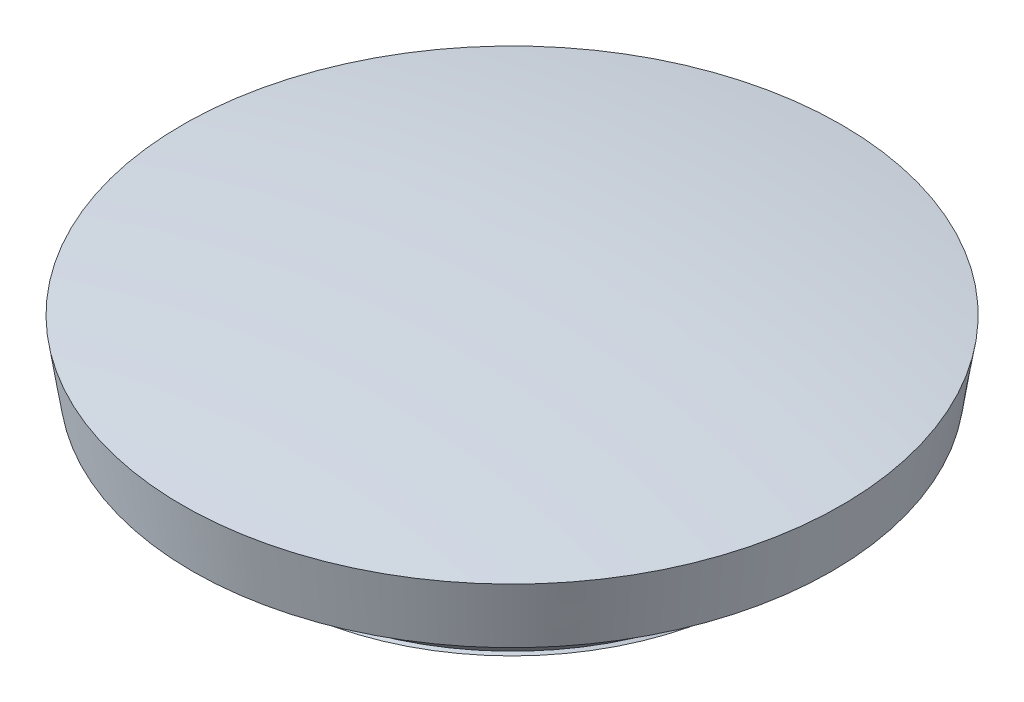
SolidWorks part; units mm, degrees
ref_plane "Front Plane" through (0, 0, 0) normal (0, 0, 1) x (1, 0, 0)
ref_plane "Top Plane" through (0, 0, 0) normal (0, 1, 0) x (1, 0, 0)
ref_plane "Right Plane" through (0, 0, 0) normal (1, 0, 0) x (0, 0, -1)
sketch "Sketch1" plane through (0, 0, 0) normal (1, 0, 0) x (0, 0, -1)
  line L0 (26.0878, 274.978) -> (26.0878, 232.1195) construction
  line L2 (40.135, 302.9291) -> (40.135, 295.6281) construction
  line L5 (0, 324) -> (3.2968, 324) construction
  line L7 (21.6442, 186.0993) -> (0, 186.0993) construction
  line L9 (26.0878, 262.3641) -> (26.0878, 259.4973) construction
  line L16 (0, 0) -> (51.9362, 327.9125) construction
  line L17 (0, 324) -> (0, 332) construction
  line L18 (26.0878, 274.978) -> (26.0878, 268.978) construction
  line L19 (26.0878, 268.978) -> (26.0878, 248.978) construction
  line L20 (26.0878, 268.978) -> (42.6019, 268.978) construction
  line L21 (26.0878, 274.978) -> (43.5522, 274.978) construction
  line L22 (26.0878, 248.978) -> (39.4342, 248.978) construction
  line L23 (0, 0) -> (-51.9362, 327.9125) construction
  line L24 (-47.4003, 299.274) -> (-47.4003, 268.978) construction
  line L25 (-47.4003, 268.978) -> (-42.6019, 268.978) construction
  line L26 (40.135, 295.6281) -> (40.435, 295.6281) construction
  line L27 (0, 76.96) -> (400, 76.96) construction
  line L28 (0, 76.96) -> (-400, 76.96) construction
  line L29 (-200, 76.96) -> (-200, 183.96) construction
  line L30 (200, 76.96) -> (200, 183.96) construction
  line L31 (-200, 183.96) -> (-200, 182.57) construction
  line L32 (-200, 182.57) -> (400, 182.57) construction
  line L33 (-200, 182.57) -> (-400, 182.57) construction
  line L36 (21.6442, 186.0993) -> (21.6442, 226.0993) construction
  line L37 (0, 324) -> (0, 186.1152) construction
  line L38 (0, 186.1152) -> (0, 186.0993)
  line L39 (0, 0) -> (-2, 0) construction
  line L40 (-2, 0) -> (49.9843, 328.2157) construction
  line L41 (51.9362, 327.9125) -> (49.9362, 327.9125) construction
  line L42 (26.0878, 274.978) -> (26.3878, 274.978) construction
  line L43 (26.0878, 274.978) -> (26.0878, 273.978) construction
  line L44 (26.2311, 276.2681) -> (26.5311, 276.2681) construction
  line L45 (26.6611, 277.4147) -> (26.9611, 277.4147) construction
  line L46 (27.2344, 278.5614) -> (27.5344, 278.5614) construction
  line L47 (27.9512, 279.4215) -> (28.2512, 279.4215) construction
  line L48 (28.9545, 280.5682) -> (29.2545, 280.5682) construction
  line L49 (29.8146, 281.4282) -> (30.1146, 281.4282) construction
  line L50 (30.8179, 282.4316) -> (31.1179, 282.4316) construction
  line L51 (31.8213, 283.2917) -> (32.1213, 283.2917) construction
  line L52 (32.8246, 284.2951) -> (33.1246, 284.2951) construction
  line L53 (33.8281, 285.2984) -> (34.1281, 285.2984) construction
  line L54 (34.9748, 286.3018) -> (35.2748, 286.3018) construction
  line L55 (35.9781, 287.3051) -> (36.2781, 287.3051) construction
  line L56 (36.8382, 288.1652) -> (37.1382, 288.1652) construction
  line L57 (37.8416, 289.3119) -> (38.1416, 289.3119) construction
  line L58 (38.5582, 290.4586) -> (38.8582, 290.4586) construction
  line L59 (39.1315, 291.7487) -> (39.4315, 291.7487) construction
  line L60 (39.5617, 292.8954) -> (39.8617, 292.8954) construction
  line L61 (39.8483, 294.0421) -> (40.1483, 294.0421) construction
  line L63 (40.135, 302.9291) -> (40.435, 302.9291) construction
  line L64 (26.0878, 273.978) -> (26.3878, 273.978) construction
  line L68 (0, 332) -> (36.0261, 332) construction
  line L69 (36.0261, 332) -> (36.0261, 309.4264) construction
  line L70 (36.0261, 309.4264) -> (48.951, 321.6917) construction
  line L71 (36.0261, 309.4264) -> (49.0083, 309.4264) construction
  line L73 (36.0261, 309.4264) -> (46.0928, 318.9794) construction
  line L74 (46.0928, 318.9794) -> (46.0928, 386.8005) construction
  line L75 (46.0928, 318.9794) -> (19.4833, 320.3739) construction
  line L76 (19.4833, 320.3739) -> (20.8454, 323.7133) construction
  line L77 (19.4833, 320.3739) -> (28.7426, 316.597) construction
  line L78 (19.4833, 320.3739) -> (10.2239, 324.1508) construction
  line L79 (10.2239, 324.1508) -> (9.7753, 323.0511) construction
  line L80 (28.7426, 316.597) -> (28.4187, 315.803) construction
  arc A0 (-298.7691, 144.7791) -> (305.6579, 129.6043) centre (0, 0) cw construction
  spline S0 degree 3 poles (21.6442, 226.0993) (22.3362, 225.9573) (23.1249, 226.5484) (24.2443, 227.206) (25.0066, 227.971) (25.5796, 228.9526) (25.8622, 230.3928) (26.0228, 231.4438) (26.0878, 232.1195) knots 0 0 0 0 0.223849 0.348959 0.47164 0.61152 0.754586 1 1 1 1 construction
  spline S1 degree 3 poles (3.2968, 324) (4.1972, 323.8396) (5.699, 323.816) (7.6935, 323.4297) (9.2722, 323.1563) (10.7507, 322.8538) (12.1816, 322.5577) (13.6372, 322.313) (14.8643, 321.9117) (15.9115, 321.5662) (16.81, 321.2491) (17.7339, 321.0149) (18.8379, 320.6416) (19.931, 320.1935) (21.0686, 319.6948) (22.141, 319.2627) (23.2156, 318.6856) (24.4371, 318.1163) (25.6762, 317.3518) (27.1066, 316.7518) (28.4318, 315.7832) (29.7322, 314.8939) (31.058, 313.93) (32.1959, 312.8581) (33.3378, 311.8503) (34.4539, 310.9646) (35.3895, 309.8867) (36.5078, 309.0949) (37.2942, 308.0208) (38.1233, 307.1238) (38.9048, 306.0961) (39.4724, 304.6349) (40.2774, 303.734) (40.135, 302.9291) knots 0 0 0 0 0.061585 0.100795 0.136831 0.1697 0.202569 0.235438 0.269088 0.289473 0.309858 0.333319 0.353706 0.388423 0.412965 0.437514 0.46634 0.495168 0.528354 0.564387 0.59925 0.638593 0.670824 0.709635 0.743897 0.773612 0.805519 0.839783 0.864953 0.89467 0.922395 0.951224 1 1 1 1 construction
  spline S2 degree 3 poles (40.135, 295.6188) (39.9636, 294.7131) (39.7869, 293.3689) (39.1095, 291.6901) (38.6019, 290.4599) (37.8418, 289.2392) (36.9195, 288.2279) (35.9232, 287.2651) (34.974, 286.2515) (33.8311, 285.3463) (32.8233, 284.2966) (31.8701, 283.2868) (30.7668, 282.4387) (29.8742, 281.4644) (28.8604, 280.5152) (28.0567, 279.5119) (27.1438, 278.5569) (26.4968, 277.0287) (26.0081, 275.8567) (26.0878, 274.978) knots 0 0 0 0 0.108356 0.15601 0.210945 0.263562 0.322855 0.370186 0.425399 0.484692 0.539909 0.595126 0.646549 0.701764 0.749093 0.808384 0.85195 0.901837 1 1 1 1 construction
  dimension "D2" = 2
  dimension "D4" = 8
  dimension "D5" = 2
  dimension "D6" = 36.0261
  dimension "D8" = 70.809
  dimension "D9" = 6
  dimension "D10" = 20
  dimension "D11" = 1.1877
  dimension "D12" = 0.8575
  dimension "D13" = 255.04
  dimension "D14" = 107
  dimension "D15" = 107
  dimension "D16" = 332
  dimension "D17" = 105.61
  dimension "D18" = 105.61
  dimension "D19" = 40
  dimension "D20" = 90
  dimension "D21" = 46.5
sketch "gel" plane through (0, 0, 0) normal (1, 0, 0) x (0, 0, -1)
  line L0 (0, 0) -> (0, 354.6797) construction
  line L2 (-2, 0) -> (-2.5, 0) construction
  line L5 (-2.5, 0) -> (49.496, 328.2897) construction
  line L12 (45.7486, 319.3421) -> (35.6819, 309.7891)
  line L13 (36.0261, 309.4264) -> (35.6819, 309.7891)
  line L14 (46.0928, 318.9794) -> (45.7486, 319.3421)
  line L20 (3.2968, 324) -> (0, 324)
  line L25 (0, 332) -> (0, 324)
  line L26 (46.0928, 318.9794) -> (48.0214, 318.9794)
  line L27 (49.496, 328.2897) -> (48.0214, 318.9794)
  arc A2 (305.6579, 129.6043) -> (-298.7691, 144.7791) centre (0, 0) ccw construction
  arc A3 (0, 332) -> (49.496, 328.2897) centre (0, 0) cw
  spline S1 degree 3 poles (36.0261, 309.4264) (35.4186, 309.8648) (34.6627, 310.7913) (33.3388, 311.8514) (32.1956, 312.8578) (31.058, 313.93) (29.7447, 314.8851) (28.4438, 315.7737) (27.1206, 316.7455) (25.6762, 317.3519) (24.4371, 318.1163) (23.2156, 318.6856) (22.141, 319.2627) (21.0686, 319.6948) (19.931, 320.1935) (18.8379, 320.6416) (17.7339, 321.0149) (16.81, 321.2491) (15.9115, 321.5662) (14.8643, 321.9117) (13.6372, 322.313) (12.1816, 322.5577) (10.7507, 322.8538) (9.2722, 323.1563) (7.6935, 323.4297) (5.699, 323.816) (4.1972, 323.8396) (3.2968, 324) knots 0 0 0 0 0.060955 0.097024 0.138613 0.185724 0.224847 0.271347 0.314921 0.35866 0.398942 0.433936 0.468926 0.498725 0.528515 0.570655 0.595402 0.62388 0.648625 0.673368 0.714215 0.754113 0.79401 0.833909 0.877651 0.925245 1 1 1 1
revolve "Revolve10" add sketch "gel" angle 360 about L0
